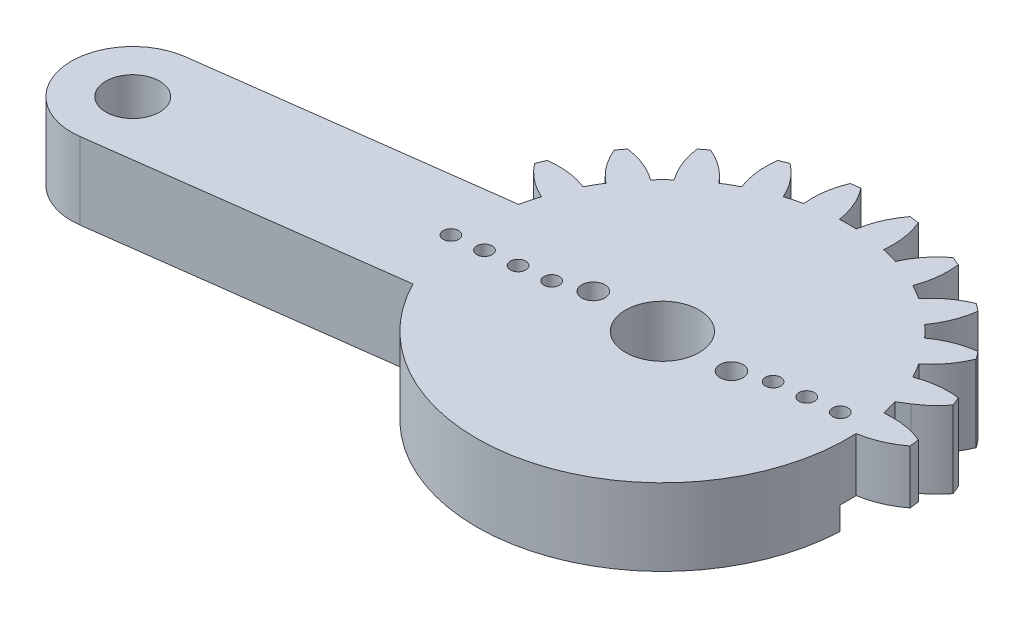
SolidWorks part; units mm, degrees
ref_plane "Front Plane" through (0, 0, 0) normal (0, 0, 1) x (1, 0, 0)
ref_plane "Top Plane" through (0, 0, 0) normal (0, 1, 0) x (1, 0, 0)
ref_plane "Right Plane" through (0, 0, 0) normal (1, 0, 0) x (0, 0, -1)
ref_plane "Plane1" through (0, 4, 0) normal (0, 1, 0) x (1, 0, 0)
sketch "Sketch1" plane through (0, 4, 0) normal (0, 1, 0) x (1, 0, 0)
  line L0 (1.4381, 3.6001) -> (2.0816, 4)
  line L1 (-21.9429, 2.4762) -> (-41.1154, -0.0479)
  line L2 (-40.0712, -7.9795) -> (-20.8986, -5.4553)
  circle A0 centre (-40.5933, -4.0137) radius 1.75
  arc A1 (4.3495, 2.2179) -> (1.7031, 2.6025) centre (2.274, -2.7673) ccw
  arc A2 (1.7031, 2.6025) -> (1.4381, 3.6001) centre (-10.1063, 0) ccw
  arc A3 (2.0816, 4) -> (3.5217, 5.3071) centre (-0.7683, 8.5867) ccw
  arc A4 (3.5217, 5.3071) -> (3.2829, 5.8838) centre (-10.1063, 0) ccw
  arc A5 (3.2829, 5.8838) -> (0.6271, 5.5703) centre (2.5684, 0.5313) ccw
  arc A6 (0.6271, 5.5703) -> (0.0844, 6.5103) centre (-10.1063, 0) ccw
  arc A7 (0.0844, 6.5103) -> (1.6838, 8.6535) centre (-3.3089, 10.711) ccw
  arc A8 (1.6838, 8.6535) -> (1.3038, 9.1487) centre (-10.1063, 0) ccw
  arc A9 (1.3038, 9.1487) -> (-1.1803, 8.1585) centre (1.999, 3.7936) ccw
  arc A10 (-1.1803, 8.1585) -> (-1.9479, 8.926) centre (-10.1063, 0) ccw
  arc A11 (-1.9479, 8.926) -> (-0.9576, 11.4102) centre (-6.3127, 12.1053) ccw
  arc A12 (-0.9576, 11.4102) -> (-1.4528, 11.7901) centre (-10.1063, 0) ccw
  arc A13 (-1.4528, 11.7901) -> (-3.596, 10.1907) centre (0.6046, 6.7975) ccw
  arc A14 (-3.596, 10.1907) -> (-4.5361, 10.7334) centre (-10.1063, 0) ccw
  arc A15 (-4.5361, 10.7334) -> (-4.2225, 13.3892) centre (-9.5751, 12.6747) ccw
  arc A16 (-4.2225, 13.3892) -> (-4.7992, 13.6281) centre (-10.1063, 0) ccw
  arc A17 (-4.7992, 13.6281) -> (-6.4554, 11.5285) centre (-1.5196, 9.3381) ccw
  arc A18 (-6.4554, 11.5285) -> (-7.5039, 11.8094) centre (-10.1063, 0) ccw
  arc A19 (-7.5039, 11.8094) -> (-7.8884, 14.4558) centre (-12.8736, 12.3803) ccw
  arc A20 (-7.8884, 14.4558) -> (-8.5072, 14.5373) centre (-10.1063, 0) ccw
  arc A21 (-8.5072, 14.5373) -> (-9.5636, 12.0806) centre (-4.2291, 11.2423) ccw
  arc A22 (-9.5636, 12.0806) -> (-10.6491, 12.0806) centre (-10.1063, 0) ccw
  arc A23 (-10.6491, 12.0806) -> (-11.7054, 14.5373) centre (-15.9836, 11.2423) ccw
  arc A24 (-11.7054, 14.5373) -> (-12.3243, 14.4558) centre (-10.1063, 0) ccw
  arc A25 (-12.3243, 14.4558) -> (-12.7088, 11.8094) centre (-7.3391, 12.3803) ccw
  arc A26 (-12.7088, 11.8094) -> (-13.7573, 11.5285) centre (-10.1063, 0) ccw
  arc A27 (-13.7573, 11.5285) -> (-15.4135, 13.6281) centre (-18.6931, 9.3381) ccw
  arc A28 (-15.4135, 13.6281) -> (-15.9901, 13.3892) centre (-10.1063, 0) ccw
  arc A29 (-15.9901, 13.3892) -> (-15.6766, 10.7334) centre (-10.6376, 12.6747) ccw
  arc A30 (-15.6766, 10.7334) -> (-16.6166, 10.1907) centre (-10.1063, 0) ccw
  arc A31 (-16.6166, 10.1907) -> (-18.7599, 11.7901) centre (-20.8173, 6.7975) ccw
  arc A32 (-18.7599, 11.7901) -> (-19.255, 11.4102) centre (-10.1063, 0) ccw
  arc A33 (-19.255, 11.4102) -> (-18.2648, 8.926) centre (-13.9, 12.1053) ccw
  arc A34 (-18.2648, 8.926) -> (-19.0324, 8.1585) centre (-10.1063, 0) ccw
  arc A35 (-19.0324, 8.1585) -> (-21.5165, 9.1487) centre (-22.2117, 3.7936) ccw
  arc A36 (-21.5165, 9.1487) -> (-21.8965, 8.6535) centre (-10.1063, 0) ccw
  arc A37 (-21.8965, 8.6535) -> (-20.2971, 6.5103) centre (-16.9038, 10.711) ccw
  arc A38 (-20.2971, 6.5103) -> (-20.8398, 5.5703) centre (-10.1063, 0) ccw
  arc A39 (-20.8398, 5.5703) -> (-23.4956, 5.8838) centre (-22.7811, 0.5313) ccw
  arc A40 (-23.4956, 5.8838) -> (-23.7344, 5.3071) centre (-10.1063, 0) ccw
  arc A41 (-23.7344, 5.3071) -> (-21.6348, 3.6509) centre (-19.4444, 8.5867) ccw
  arc A42 (-21.6348, 3.6509) -> (-21.9429, 2.4762) centre (-10.1063, 0) ccw
  arc A43 (-41.1154, -0.0479) -> (-40.0712, -7.9795) centre (-40.5933, -4.0137) ccw
  arc A44 (-20.8986, -5.4553) -> (1.9742, 0.5427) centre (-10.1063, 0) ccw
  arc A45 (1.9742, 0.5427) -> (4.431, 1.5991) centre (1.1359, 5.8773) ccw
  arc A46 (4.431, 1.5991) -> (4.3495, 2.2179) centre (-10.1063, 0) ccw
  circle A47 centre (-10.1063, 0) radius 2.4
  circle A48 centre (-5.6063, 0) radius 0.75
  circle A49 centre (-14.6063, 0) radius 0.75
  dimension "D1" = 3.5
  dimension "D2" = 1.5
  dimension "D3" = 4.8
  dimension "D4" = 1.5
  dimension "D5" = 5.4
  dimension "D6" = 12.0927
  dimension "D7" = 5.4
  dimension "D8" = 14.625
  dimension "D9" = 5.4
  dimension "D10" = 0.0844
  dimension "D11" = 5.4
  dimension "D12" = 0.6046
  dimension "D13" = 5.4
  dimension "D14" = 0.6271
  dimension "D15" = 5.4
  dimension "D16" = 1.1359
  dimension "D17" = 5.4
  dimension "D18" = 1.3038
  dimension "D19" = 5.4
  dimension "D20" = 1.4381
  dimension "D21" = 5.4
  dimension "D22" = 1.6838
  dimension "D23" = 5.4
  dimension "D24" = 1.7031
  dimension "D25" = 5.4
  dimension "D26" = 1.9742
  dimension "D27" = 5.4
  dimension "D28" = 1.999
  dimension "D29" = 5.4
  dimension "D30" = 2.0816
  dimension "D31" = 5.4
  dimension "D32" = 2.274
  dimension "D33" = 5.4
  dimension "D34" = 2.5684
  dimension "D35" = 5.4
  dimension "D36" = 3.2829
  dimension "D37" = 5.4
  dimension "D38" = 3.5217
  dimension "D39" = 5.4
  dimension "D40" = 0.9576
  dimension "D41" = 5.4
  dimension "D42" = 1.4528
  dimension "D43" = 5.4
  dimension "D44" = 1.5196
  dimension "D45" = 5.4
  dimension "D46" = 1.9479
  dimension "D47" = 4
  dimension "D48" = 4.2225
  dimension "D49" = 5.4
  dimension "D50" = 4.2291
  dimension "D51" = 4.5361
  dimension "D52" = 4.7992
  dimension "D53" = 5.6063
  dimension "D54" = 7.3391
  dimension "D55" = 7.5039
  dimension "D56" = 7.8884
  dimension "D57" = 8.5072
  dimension "D58" = 10.6376
  dimension "D59" = 10.6491
  dimension "D60" = 11.7054
  dimension "D61" = 12.3243
  dimension "D62" = 13.7573
  dimension "D63" = 13.9
  dimension "D64" = 14.6063
  dimension "D65" = 15.4135
  dimension "D66" = 15.6766
  dimension "D67" = 16.6166
  dimension "D68" = 16.9038
  dimension "D69" = 18.2648
  dimension "D70" = 18.7599
  dimension "D71" = 19.0324
  dimension "D72" = 19.4444
  dimension "D73" = 20.2971
  dimension "D74" = 20.8398
  dimension "D75" = 20.8986
  dimension "D76" = 21.5165
  dimension "D77" = 21.6348
  dimension "D78" = 21.9429
  dimension "D79" = 22.7811
  dimension "D80" = 40.0712
  dimension "D81" = 40.5933
  dimension "D82" = 0.5313
extrude "Boss-Extrude1" add sketch "Sketch1" against normal blind 5
sketch "Sketch2" plane through (0, -1, 0) normal (0, -1, 0) x (1, 0, 0)
  circle A14 centre (-22.4255, 1.4568) radius 0.5
  circle A15 centre (-22.4255, 1.4568) radius 0.5
  circle A16 centre (-16.5564, 0.7628) radius 0.5
  circle A17 centre (-16.5564, 0.7628) radius 0.5
  circle A22 centre (-20.4691, 1.2255) radius 0.5
  circle A23 centre (-20.4691, 1.2255) radius 0.5
  circle A24 centre (-18.5128, 0.9941) radius 0.5
  circle A25 centre (-18.5128, 0.9941) radius 0.5
  circle A28 centre (-3.6563, -0.7628) radius 0.5
  circle A29 centre (-3.6563, -0.7628) radius 0.5
  circle A30 centre (-1.6999, -0.9941) radius 0.5
  circle A31 centre (-1.6999, -0.9941) radius 0.5
  circle A32 centre (0.2564, -1.2255) radius 0.5
  circle A33 centre (0.2564, -1.2255) radius 0.5
  circle A38 centre (-10.1063, 0) radius 2.25
  circle A39 centre (-10.1063, 0) radius 2.25
  dimension "D1" = 0
  dimension "D2" = 0
  dimension "D5" = 0
  dimension "D6" = 0
  dimension "D8" = 0
  dimension "D9" = 0
  dimension "D10" = 0
  dimension "D13" = 0
extrude "Cut-Extrude1" cut sketch "Sketch2" against normal through all
sketch "Sketch3" plane through (0, -1, 0) normal (0, -1, 0) x (1, 0, 0)
  line L4 (4.0661, 0.0806) -> (-7.6564, 2.4291)
  line L5 (-8.2906, -2.9335) -> (3.6563, -3.3841)
  line L6 (-24.2788, -0.0806) -> (-12.5562, -2.4291)
  line L7 (-11.9221, 2.9335) -> (-23.869, 3.3841)
  line L8 (4.0661, 0.0806) -> (-7.6564, 2.4291)
  line L9 (-8.2906, -2.9335) -> (3.6563, -3.3841)
  line L10 (-24.2788, -0.0806) -> (-12.5562, -2.4291)
  line L11 (-11.9221, 2.9335) -> (-23.869, 3.3841)
  arc A4 (-7.6564, 2.4291) -> (-11.9221, 2.9335) centre (-10.1063, 0) ccw
  arc A5 (3.6563, -3.3841) -> (4.0661, 0.0806) centre (3.7223, -1.6353) ccw
  arc A6 (-12.5562, -2.4291) -> (-8.2906, -2.9335) centre (-10.1063, 0) ccw
  arc A7 (-23.869, 3.3841) -> (-24.2788, -0.0806) centre (-23.935, 1.6353) ccw
  arc A8 (-7.6564, 2.4291) -> (-11.9221, 2.9335) centre (-10.1063, 0) ccw
  arc A9 (3.6563, -3.3841) -> (4.0661, 0.0806) centre (3.7223, -1.6353) ccw
  arc A10 (-12.5562, -2.4291) -> (-8.2906, -2.9335) centre (-10.1063, 0) ccw
  arc A11 (-23.869, 3.3841) -> (-24.2788, -0.0806) centre (-23.935, 1.6353) ccw
  dimension "D1" = 0
extrude "Cut-Extrude2" cut sketch "Sketch3" against normal blind 1.5
